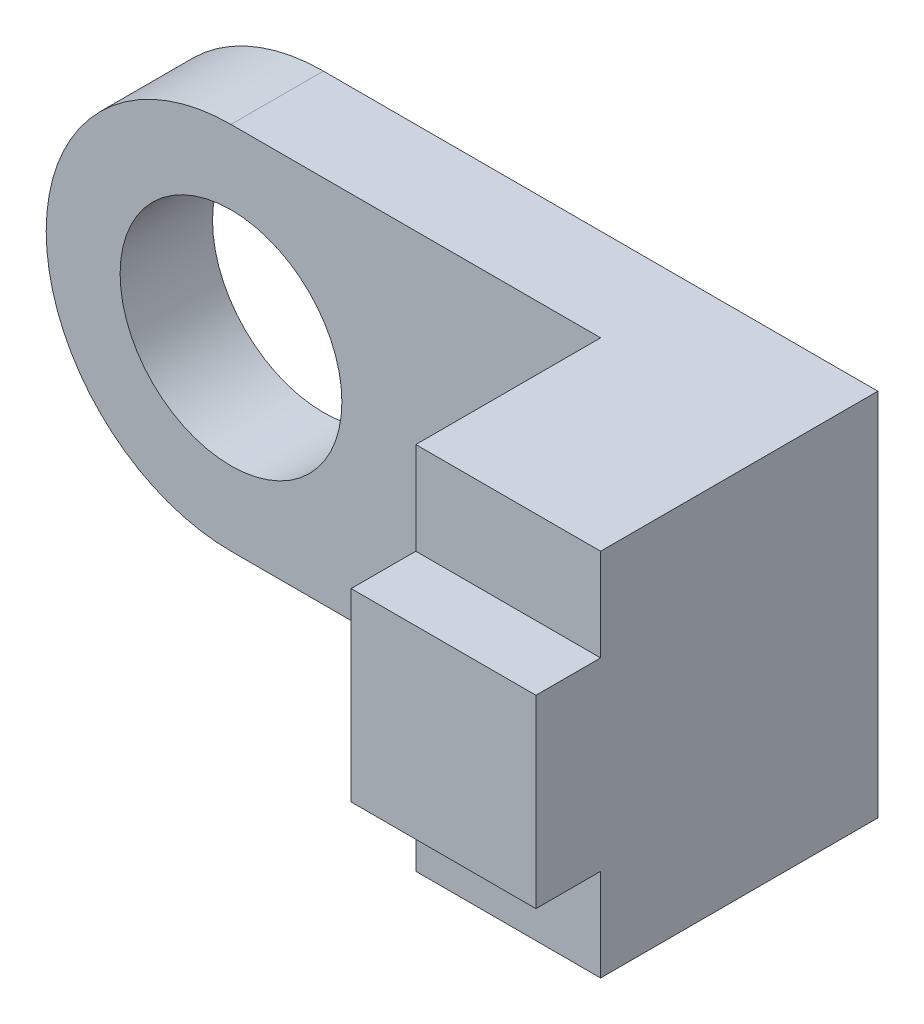
SolidWorks part; units mm, degrees
ref_plane "Front Plane" through (0, 0, 0) normal (0, 0, 1) x (1, 0, 0)
ref_plane "Top Plane" through (0, 0, 0) normal (0, 1, 0) x (1, 0, 0)
ref_plane "Right Plane" through (0, 0, 0) normal (1, 0, 0) x (0, 0, -1)
sketch "Sketch1" plane through (0, 0, 0) normal (0, 0, 1) x (1, 0, 0)
  line L1 (30, -20) -> (-30, -20)
  line L2 (30, -20) -> (30, 20)
  line L3 (30, 20) -> (-30, 20)
  line L5 (30, -20) -> (-30, 20) construction
  line L6 (30, 20) -> (-30, -20) construction
  arc A0 (-30, 20) -> (-30, -20) centre (-30, 0) ccw
  circle A1 centre (-30, 0) radius 12
  point P0 (0, 0)
  point P2 (0, 0)
  point P10 (0, 0)
  point P11 (-93.2751, -0.3207)
  point P12 (0, 0)
  dimension "D3" = 24
  dimension "D4" = 20
  dimension "D1" = 60
  dimension "D2" = 40
  dimension "D5" = 60
extrude "Boss-Extrude1" add sketch "Sketch1" along normal blind 10
sketch "Sketch2" plane through (0, 0, 10) normal (0, 0, 1) x (1, 0, 0)
  line L0 (-30, -20) -> (30, -20) construction
  line L1 (30, 20) -> (10, 20)
  line L2 (30, 20) -> (30, -20)
  line L3 (30, -20) -> (10, -20)
  line L4 (10, 20) -> (10, -20)
  dimension "D1" = 20
extrude "Boss-Extrude2" add sketch "Sketch2" along normal blind 20
sketch "Sketch3" plane through (0, 0, 30) normal (0, 0, 1) x (1, 0, 0)
  line L0 (30, -20) -> (30, 20) construction
  line L1 (30, 10) -> (10, 10)
  line L2 (30, 10) -> (30, -10)
  line L3 (30, -10) -> (10, -10)
  line L4 (10, 10) -> (10, -10)
  line L5 (10, 20) -> (10, -20) construction
  line L6 (30, 20) -> (10, 20) construction
  dimension "D1" = 10
  dimension "D2" = 20
extrude "Boss-Extrude3" add sketch "Sketch3" along normal blind 7
